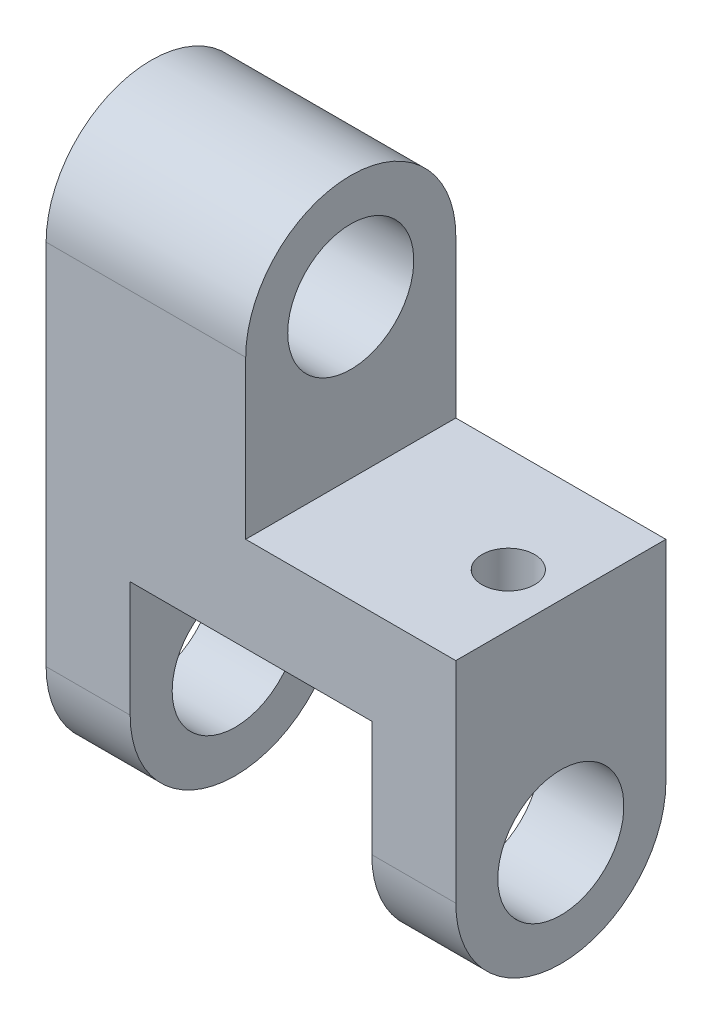
SolidWorks part; units mm, degrees
material "Литая легированная сталь"
ref_plane "Спереди" through (0, 0, 0) normal (0, 0, 1) x (1, 0, 0)
ref_plane "Сверху" through (0, 0, 0) normal (0, 1, 0) x (1, 0, 0)
ref_plane "Справа" through (0, 0, 0) normal (1, 0, 0) x (0, 0, -1)
sketch "Эскиз1" plane through (0, 0, 0) normal (1, 0, 0) x (0, 0, -1)
  line L0 (0, 17.5) -> (0, -17.5) construction
  line L1 (10, 17.5) -> (10, -17.5)
  line L2 (-10, 17.5) -> (-10, -17.5)
  line L3 (-17.287, 0) -> (16.9614, 0) construction
  arc A0 (10, 17.5) -> (-10, 17.5) centre (0, 17.5) ccw
  arc A1 (-10, -17.5) -> (10, -17.5) centre (0, -17.5) ccw
  circle A2 centre (0, 17.5) radius 6
  circle A3 centre (0, -17.5) radius 6
  point P3 (0, 0)
  dimension "D1" = 55
  dimension "D3" = 12
  dimension "D2" = 20
extrude "Бобышка-Вытянуть1" add sketch "Эскиз1" along normal blind 39
sketch "Эскиз2" plane through (0, 0, 0) normal (0, 0, 1) x (1, 0, 0)
  line L0 (0, 17.5) -> (0, -17.5) construction
  line L1 (8, -6.5) -> (31, -6.5)
  line L2 (8, -6.5) -> (8, -40.5924)
  line L3 (8, -40.5924) -> (31, -40.5924)
  line L4 (31, -6.5) -> (31, -40.5924)
  line L5 (39, 17.5) -> (39, -17.5) construction
  line L6 (0, -27.5) -> (39, -27.5) construction
  dimension "D1" = 8
  dimension "D2" = 8
  dimension "D3" = 21
extrude "Вырез-Вытянуть1" cut sketch "Эскиз2" against normal through all and the other way through all
sketch "Эскиз3" plane through (0, 0, 0) normal (0, 0, 1) x (1, 0, 0)
  line L0 (0, 17.5) -> (0, -17.5) construction
  line L1 (19, 35.0973) -> (62.7132, 35.0973)
  line L2 (19, 35.0973) -> (19, 2.5)
  line L3 (19, 2.5) -> (62.7132, 2.5)
  line L4 (62.7132, 35.0973) -> (62.7132, 2.5)
  line L5 (31, -6.5) -> (8, -6.5) construction
  dimension "D1" = 19
  dimension "D2" = 9
extrude "Вырез-Вытянуть2" cut sketch "Эскиз3" against normal through all and the other way through all
sketch "Эскиз4" plane through (0, 2.5, 0) normal (0, 1, 0) x (1, 0, 0)
  line L0 (23.1159, 0) -> (39, 0) construction
  line L1 (39, -10) -> (39, 10) construction
  circle A0 centre (34, 0) radius 2.5
  dimension "D1" = 5
  dimension "D2" = 5
extrude "Вырез-Вытянуть3" cut sketch "Эскиз4" against normal blind 12
ref_plane "Средняя плоскость петли" through (19.5, 0, 0) normal (1, 0, 0) x (0, 0, -1)
